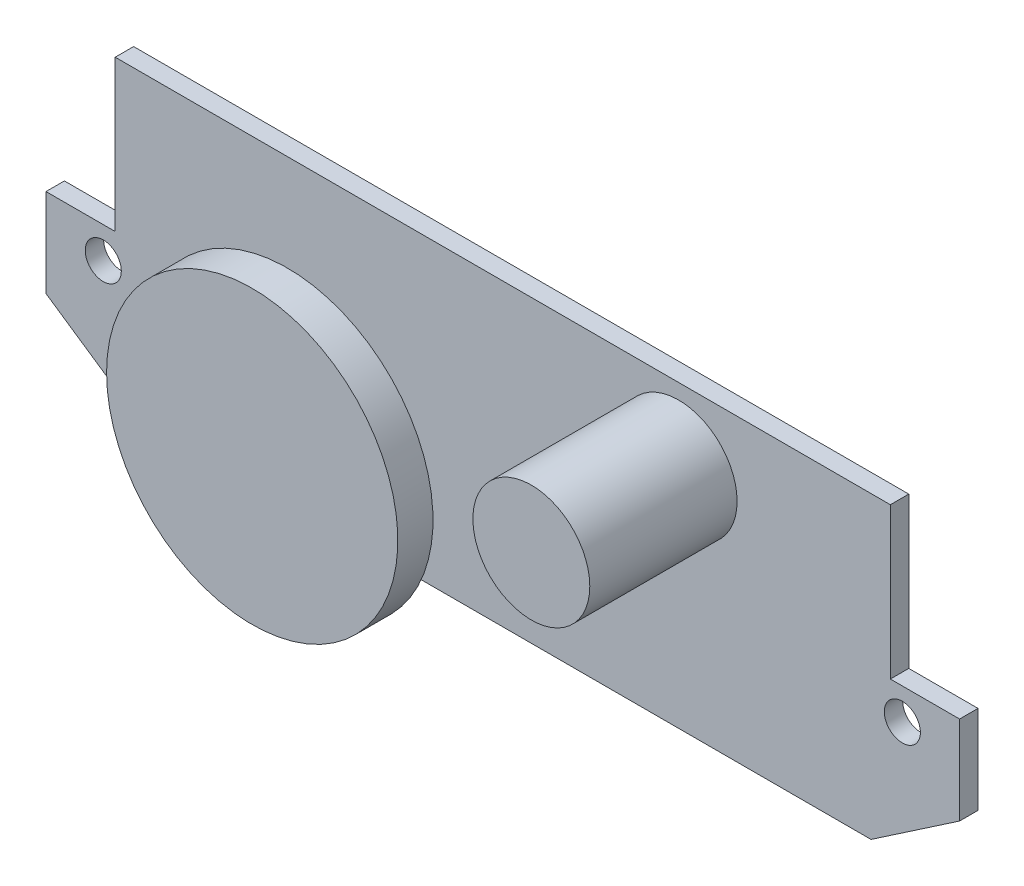
SolidWorks part; units mm, degrees
ref_plane "Front Plane" through (0, 0, 0) normal (0, 0, 1) x (1, 0, 0)
ref_plane "Top Plane" through (0, 0, 0) normal (0, 1, 0) x (1, 0, 0)
ref_plane "Right Plane" through (0, 0, 0) normal (1, 0, 0) x (0, 0, -1)
sketch "Sketch1" plane through (0, 0, 0) normal (0, 0, 1) x (1, 0, 0)
  line L0 (21.05, 0) -> (-21.05, 0)
  line L1 (-21.05, 0) -> (-21.05, -8.2)
  line L2 (-91.1495, 30.6685) -> (-90.9481, 30.7693)
  line L3 (-21.05, -8.2) -> (-24.81, -8.2)
  line L4 (-24.81, -8.2) -> (-24.81, -13)
  line L5 (-24.81, -13) -> (-20, -16.27)
  line L6 (-20, -16.27) -> (20, -16.27)
  line L7 (0, 0) -> (0, -16.27) construction
  line L8 (24.81, -13) -> (20, -16.27)
  line L9 (24.81, -8.2) -> (24.81, -13)
  line L10 (21.05, -8.2) -> (24.81, -8.2)
  line L11 (21.05, 0) -> (21.05, -8.2)
  point P4 (0, 0)
  dimension "D1" = 21.05
  dimension "D2" = 16.27
  dimension "D3" = 24.81
  dimension "D4" = 8.2
  dimension "D5" = 4.8
  dimension "D6" = 20
extrude "Boss-Extrude1" add sketch "Sketch1" along normal blind 1 contours L0 L7 L6 L8 L9 L10 L11 | L7 L0 L1 L3 L4 L5 L6
sketch "Sketch5" plane through (0, 0, 1) normal (0, 0, 1) x (1, 0, 0)
  line L0 (0, 0) -> (0, -16.27) construction
  line L1 (21.05, 0) -> (-21.05, 0) construction
  line L2 (-20, -16.27) -> (20, -16.27) construction
  circle A0 centre (-21.7, -9.9) radius 0.98
  circle A1 centre (21.7, -9.9) radius 0.98
  point P8 (21.7, -9.9)
  dimension "D1" = 1.96
  dimension "D2" = 21.7
  dimension "D3" = 9.9
extrude "Cut-Extrude1" cut sketch "Sketch5" against normal up to next
sketch "Sketch2" plane through (0, 0, 1) normal (0, 0, 1) x (1, 0, 0)
  line L0 (21.05, 0) -> (21.05, -8.2) construction
  line L1 (21.05, 0) -> (-21.05, 0) construction
  circle A0 centre (9.55, -4) radius 3.175
  dimension "D2" = 6.35
  dimension "D1" = 11.5
  dimension "D3" = 4
extrude "Boss-Extrude2" add sketch "Sketch2" along normal blind 8
sketch "Sketch3" plane through (0, 0, 1) normal (0, 0, 1) x (1, 0, 0)
  line L0 (-21.05, 0) -> (-21.05, -8.2) construction
  line L2 (21.05, 0) -> (-21.05, 0) construction
  circle A0 centre (-10.05, -11.5) radius 7.91
  point P2 (0, 0)
  point P5 (0, 0)
  dimension "D1" = 15.82
  dimension "D2" = 11
  dimension "D3" = 11.5
extrude "Boss-Extrude3" add sketch "Sketch3" along normal blind 1.91 from offset 1.65 separate body
sketch "Sketch4" plane through (0, 0, 1) normal (0, 0, 1) x (1, 0, 0)
  circle A0 centre (-10.05, -11.5) radius 5
  dimension "D1" = 10
extrude "Boss-Extrude4" add sketch "Sketch4" along normal up to next
